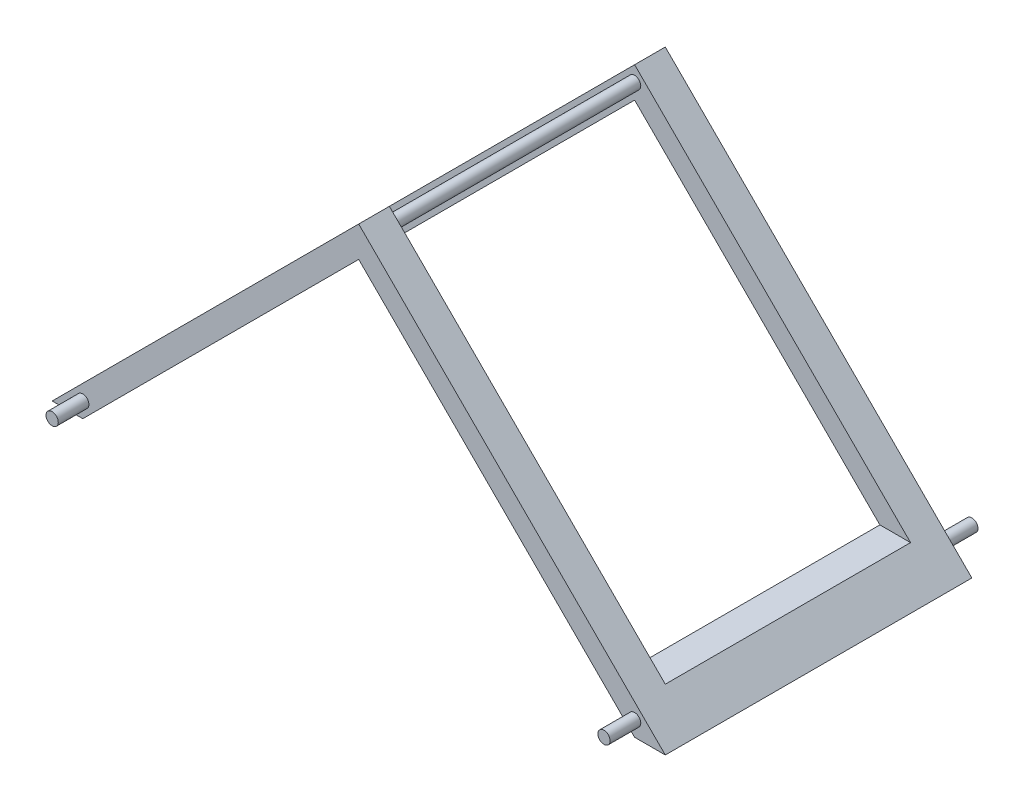
SolidWorks part; units mm, degrees
ref_plane "Front Plane" through (0, 0, 0) normal (0, 0, 1) x (1, 0, 0)
ref_plane "Top Plane" through (0, 0, 0) normal (0, 1, 0) x (1, 0, 0)
ref_plane "Right Plane" through (0, 0, 0) normal (1, 0, 0) x (0, 0, -1)
sketch "Sketch2" plane through (0, 0, 0) normal (0, 0, 1) x (1, 0, 0)
  line L0 (-500, 0) -> (0, 500)
  line L1 (0, 500) -> (500, 0)
  line L2 (500, 0) -> (450, 0)
  line L3 (450, 0) -> (0, 450)
  line L4 (0, 450) -> (-450, 0)
  line L5 (-450, 0) -> (-500, 0)
  line L6 (-500, 0) -> (500, 0) construction
  line L7 (0, 450) -> (0, 0) construction
  dimension "D1" = 1000
  dimension "D2" = 50
extrude "Boss-Extrude2" add sketch "Sketch2" along normal mid plane 500 contours L0 L1 L2 L3 L4 L5
sketch "Sketch4" plane through (0, 0, 0) normal (1, 0, 0) x (0, 0, -1)
  line L0 (-200, 500) -> (-200, 50)
  line L1 (-250, 500) -> (250, 500) construction
  line L2 (-200, 50) -> (200, 50)
  line L3 (200, 50) -> (200, 500)
  line L4 (-200, 500) -> (200, 500)
  line L5 (-250, 500) -> (250, 500) construction
  line L6 (250, 500) -> (250, 0) construction
  dimension "D1" = 450
  dimension "D2" = 400
  dimension "D3" = 50
extrude "Cut-Extrude1" cut sketch "Sketch4" against normal through all both and the other way through all
sketch "Sketch6" plane through (0, 0, 200) normal (0, 0, -1) x (-1, 0, 0)
  line L0 (0, 500) -> (0, 450) construction
  circle A0 centre (0, 475) radius 10
  dimension "D1" = 20
extrude "Boss-Extrude3" add sketch "Sketch6" along normal up to next
sketch "Sketch7" plane through (0, 0, 250) normal (0, 0, 1) x (1, 0, 0)
  line L0 (450, 0) -> (450, 50) construction
  line L1 (0, 500) -> (500, 0) construction
  circle A0 centre (450, 25) radius 10
  point P12 (450, 25)
  dimension "D1" = 20
extrude "Boss-Extrude4" add sketch "Sketch7" along normal blind 50
mirror "Mirror1" about plane through (0, 0, 0) normal (0, 0, 1) of "Boss-Extrude4"
mirror "Mirror2" about plane through (0, 0, 0) normal (1, 0, 0) of "Mirror1", "Boss-Extrude4"
